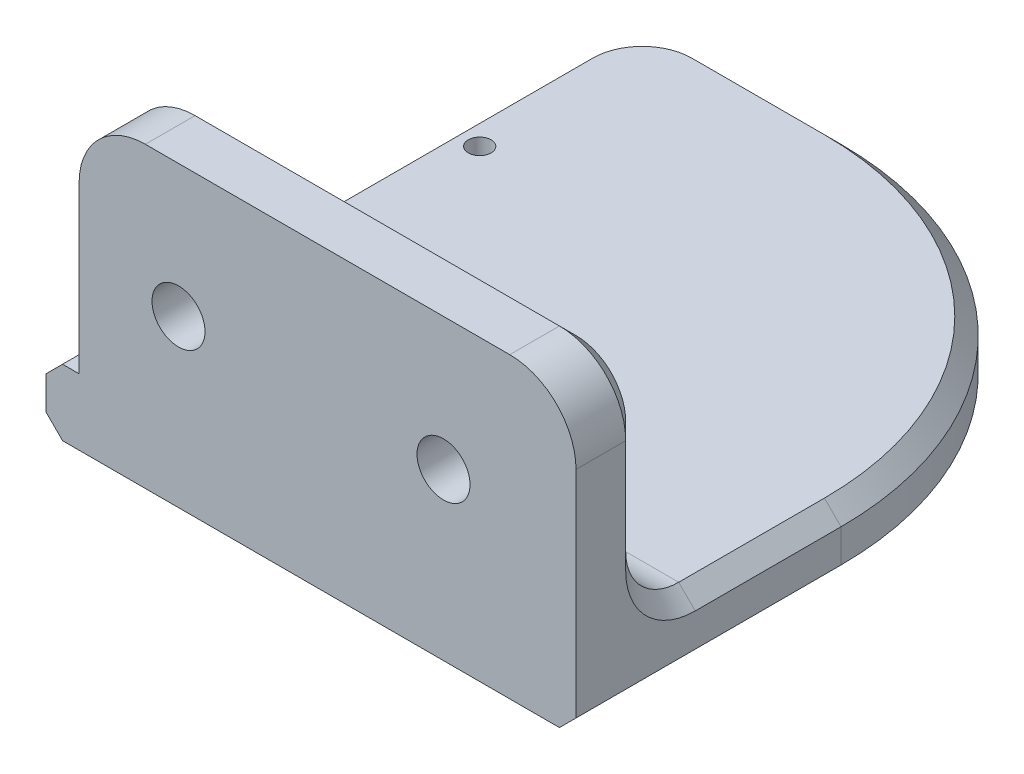
SolidWorks part; units mm, degrees
ref_plane "Front Plane" through (0, 0, 0) normal (0, 0, 1) x (1, 0, 0)
ref_plane "Top Plane" through (0, 0, 0) normal (0, 1, 0) x (1, 0, 0)
ref_plane "Right Plane" through (0, 0, 0) normal (1, 0, 0) x (0, 0, -1)
sketch "Sketch1" plane through (0, 0, 0) normal (1, 0, 0) x (0, 0, -1)
  line L0 (0, 0) -> (0, 28.575)
  line L1 (0, 28.575) -> (6.35, 28.575)
  line L2 (6.35, 28.575) -> (6.35, 6.35)
  line L3 (6.35, 6.35) -> (57.15, 6.35)
  line L4 (57.15, 6.35) -> (57.15, 0)
  line L5 (57.15, 0) -> (0, 0)
  dimension "D1" = 28.575
  dimension "D2" = 6.35
  dimension "D3" = 57.15
extrude "Boss-Extrude1" add sketch "Sketch1" along normal blind 50.8
sketch "Sketch2" plane through (0, 0, 0) normal (0, 0, 1) x (1, 0, 0)
  line L2 (50.8, 0) -> (0, 0) construction
  line L4 (25.4, 0) -> (25.4, 28.575) construction
  line L5 (50.8, 28.575) -> (0, 28.575) construction
  circle A1 centre (12.7, 15.875) radius 2.54
  circle A11 centre (38.1, 15.875) radius 2.54
  dimension "D1" = 5.08
  dimension "D2" = 12.7
  dimension "D4" = 15.875
extrude "Cut-Extrude1" cut sketch "Sketch2" against normal through all
sketch "Sketch3" plane through (0, 0, 0) normal (0, -1, 0) x (1, 0, 0)
  line L3 (0, 0) -> (0, -57.15) construction
  line L4 (50.8, 0) -> (0, 0) construction
  circle A1 centre (13.9065, -15.875) radius 1.0922
  circle A2 centre (3.4925, -38.0746) radius 1.0922
  dimension "D1" = 2.1844
  dimension "D2" = 10.414
  dimension "D3" = 22.1996
  dimension "D4" = 15.875
  dimension "D5" = 3.4925
extrude "Cut-Extrude2" cut sketch "Sketch3" against normal through all
fillet "Fillet2" radius 31.75 1 edges at (50.8, 3.175, -57.15)
sketch "Sketch4" plane through (0, 0, -6.35) normal (0, 0, -1) x (-1, 0, 0)
  line L0 (-50.8, 6.35) -> (0, 6.35) construction
  line L1 (0, 28.575) -> (-3.175, 28.575)
  line L2 (0, 28.575) -> (0, 6.35)
  line L3 (0, 6.35) -> (-3.175, 6.35)
  line L4 (-3.175, 28.575) -> (-3.175, 6.35)
  dimension "D1" = 3.175
extrude "Cut-Extrude3" cut sketch "Sketch4" against normal through all
fillet "Fillet3" radius 6.35 3 edges at (50.8, 28.575, -3.175) (3.175, 28.575, -3.175) (0, 3.175, -57.15)
fillet "Fillet4" radius 5.08 1 edges at (26.9875, 6.35, -6.35)
chamfer "Chamfer1" distance 1.5875 angle 45 17 edges at (50.8, 0, -12.7) (41.5006, 0, -47.8506) (12.7, 0, -57.15) (1.8599, 0, -55.2901) (0, 0, -25.4) (0, 6.35, -25.4) (1.8599, 6.35, -55.2901) (12.7, 6.35, -57.15) (41.5006, 6.35, -47.8506) (50.8, 6.35, -18.415) (50.8, 7.8379, -7.8379) (50.8, 16.8275, -6.35) (48.9401, 26.7151, -6.35) (26.9875, 28.575, -6.35) (5.0349, 26.7151, -6.35) (3.175, 16.8275, -6.35) (3.175, 7.8379, -7.8379)
